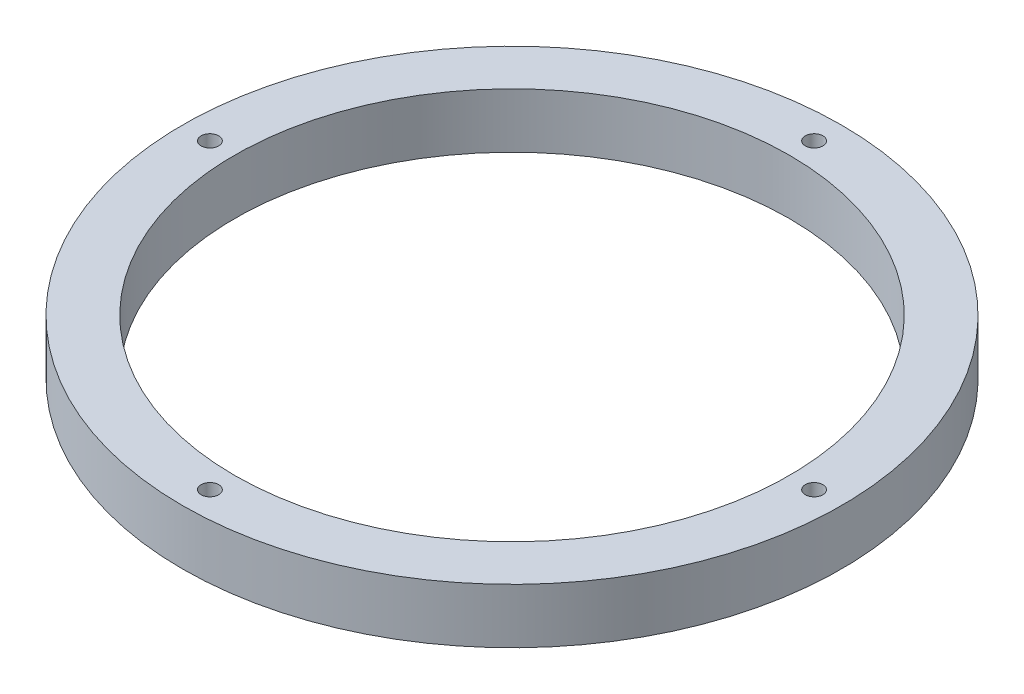
SolidWorks part; units mm, degrees
ref_plane "前视基准面" through (0, 0, 0) normal (0, 0, 1) x (1, 0, 0)
ref_plane "上视基准面" through (0, 0, 0) normal (0, 1, 0) x (1, 0, 0)
ref_plane "右视基准面" through (0, 0, 0) normal (1, 0, 0) x (0, 0, -1)
sketch "草图1" plane through (0, 0, 0) normal (0, 1, 0) x (1, 0, 0)
  circle A0 centre (0, 0) radius 60
  circle A1 centre (0, 0) radius 50.5
  circle A2 centre (0, 55) radius 1.6
  circle A3 centre (55, 0) radius 1.6
  circle A4 centre (0, -55) radius 1.6
  circle A5 centre (-55, 0) radius 1.6
  point P15 (0, 0)
  dimension "D1" = 120
  dimension "D2" = 9.5
  dimension "D3" = 3.2
  dimension "D4" = 55
  dimension "D5" = 4
extrude "凸台-拉伸1" add sketch "草图1" along normal blind 10
